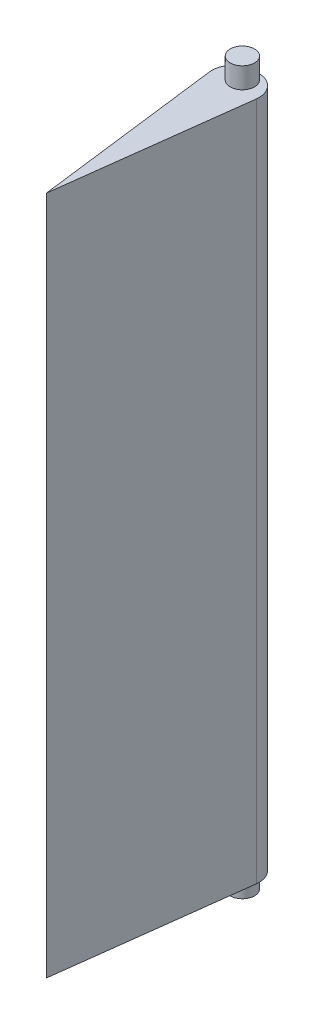
SolidWorks part; units mm, degrees
ref_plane "Front Plane" through (0, 0, 0) normal (0, 0, 1) x (1, 0, 0)
ref_plane "Top Plane" through (0, 0, 0) normal (0, 1, 0) x (1, 0, 0)
ref_plane "Right Plane" through (0, 0, 0) normal (1, 0, 0) x (0, 0, -1)
sketch "Sketch1" plane through (0, 0, 0) normal (0, 1, 0) x (1, 0, 0)
  line L0 (0, 0) -> (19.304, 0)
  line L1 (9.652, -76.835) -> (9.652, 0) construction
  line L2 (0, 0) -> (9.652, -76.835)
  line L3 (9.652, -76.835) -> (19.304, 0)
  dimension "D1" = 19.304
  dimension "D2" = 76.835
extrude "Boss-Extrude1" add sketch "Sketch1" along normal blind 248.92
fillet "Fillet1" radius 7.62 1 edges at (0, 124.46, 0)
fillet "Fillet2" radius 7.62 1 edges at (19.304, 124.46, 0)
ref_plane "Plane1" through (0, 0, 0) normal (0, -1, 0) x (-1, 0, 0)
sketch "Sketch3" plane through (0, 0, 0) normal (0, -1, 0) x (-1, 0, 0)
  line L0 (-9.652, 0) -> (-9.652, -5.08) construction
  line L1 (-10.6669, 0) -> (-8.6371, 0) construction
  circle A0 centre (-9.652, -5.08) radius 4.445
  dimension "D2" = 8.89
  dimension "D1" = 5.08
extrude "Boss-Extrude2" add sketch "Sketch3" along normal blind 7.62
ref_plane "Plane2" through (0, 248.92, 0) normal (0, 1, 0) x (1, 0, 0)
sketch "Sketch4" plane through (0, 248.92, 0) normal (0, 1, 0) x (1, 0, 0)
  line L0 (9.652, 0) -> (9.652, -5.08) construction
  line L1 (10.6669, 0) -> (8.6371, 0) construction
  circle A0 centre (9.652, -5.08) radius 4.445
  dimension "D2" = 8.89
  dimension "D1" = 5.08
extrude "Boss-Extrude4" add sketch "Sketch4" along normal blind 7.62
